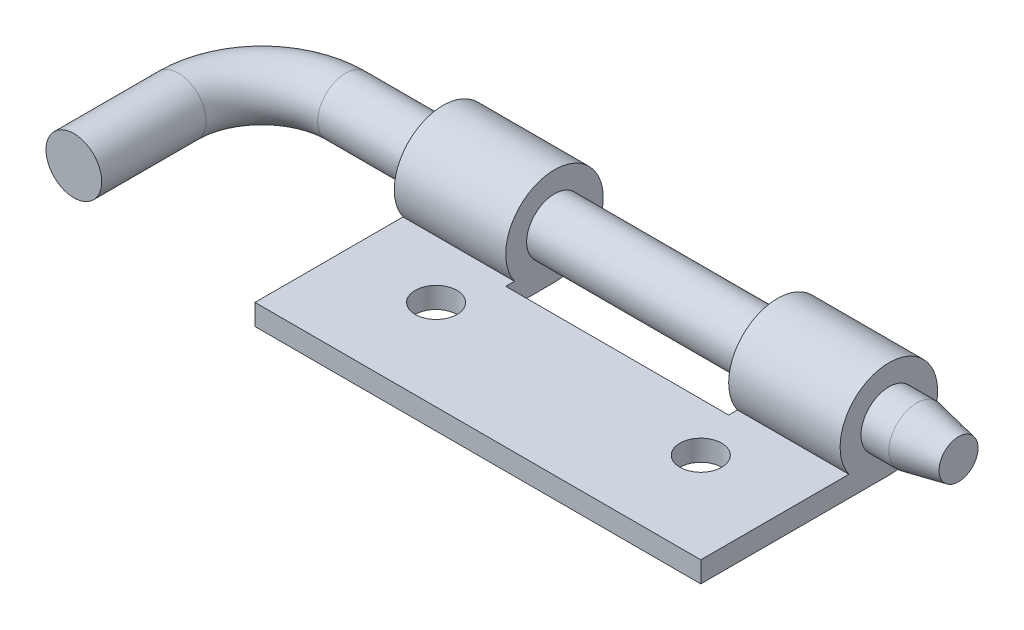
SolidWorks part; units mm, degrees
ref_plane "前视基准面" through (0, 0, 0) normal (0, 0, 1) x (1, 0, 0)
ref_plane "上视基准面" through (0, 0, 0) normal (0, 1, 0) x (1, 0, 0)
ref_plane "右视基准面" through (0, 0, 0) normal (1, 0, 0) x (0, 0, -1)
other "Configuration Table"
sketch "草图6" plane through (0, 0, 0) normal (1, 0, 0) x (0, 0, -1)
  circle A0 centre (0, 0) radius 3.5
  dimension "D1" = 7
extrude "凸台-拉伸4" add sketch "草图6" along normal blind 8
sketch "草图7" plane through (0, 0, 0) normal (-1, 0, 0) x (0, 0, 1)
  circle A0 centre (0, 0) radius 3.5 construction
  circle A1 centre (0, 0) radius 3.5
extrude "凸台-拉伸5" add sketch "草图7" against normal blind 8 from offset 24 separate body offset against normal yes
sketch "草图8" plane through (0, 0, 0) normal (0, 1, 0) x (1, 0, 0)
  line L0 (32, 3.5) -> (24, 3.5) construction
  line L1 (0, 0) -> (8, 0)
  line L2 (0, 0) -> (0, -13.5)
  line L3 (0, -13.5) -> (32, -13.5)
  line L4 (32, 0) -> (32, -13.5)
  line L5 (8, 0) -> (8, -3.5)
  line L6 (8, -3.5) -> (8, 3.5) construction
  line L7 (8, -3.5) -> (24, -3.5)
  line L8 (24, -3.5) -> (24, 0)
  line L9 (24, 3.5) -> (24, -3.5) construction
  line L10 (24, -3.5) -> (32, -3.5) construction
  line L11 (24, 0) -> (32, 0)
  circle A0 centre (25.5, -7) radius 1.5
  circle A1 centre (6.5, -7) radius 1.5
  point P9 (25.5, -8.5)
  point P10 (27, -7)
  dimension "D5" = 3
  dimension "D6" = 3
  dimension "D1" = 32
  dimension "D2" = 17
  dimension "D3" = 5
  dimension "D4" = 5
  dimension "D7" = 19
extrude "凸台-拉伸6" add sketch "草图8" along normal blind 1.5 from offset 3.5 offset against normal yes
sketch "草图9" plane through (0, 0, 0) normal (0, 1, 0) x (1, 0, 0)
  line L0 (37, 0) -> (-7, 0)
  line L1 (-13, -6) -> (-13, -13.5)
  line L6 (32, -3.5) -> (32, 3.5) construction
  line L7 (0, -13.5) -> (32, -13.5) construction
  arc A0 (-7, 0) -> (-13, -6) centre (-7, -6) ccw
  point P10 (0, 0)
  dimension "D3" = 6
  dimension "D1" = 5
  dimension "D2" = 50
ref_plane "基准面2" through (37, 0, 0) normal (1, 0, 0) x (0, 0, -1)
sketch "草图11" plane through (37, 0, 0) normal (1, 0, 0) x (0, 0, -1)
  circle A0 centre (0, 0) radius 2
  dimension "D1" = 4
sweep "扫描2" add profiles "草图11" path "草图9"
sketch "草图12" plane through (0, 0, 0) normal (0, 1, 0) x (1, 0, 0)
  line L0 (34, -2) -> (34, 2)
  line L1 (-3.85, 0) -> (3.85, 0) construction
  line L2 (37, 2) -> (32, 2) construction
  line L3 (34, 2) -> (37, 1.4)
  line L4 (37, -55) -> (37, 55) construction
  line L5 (37, 1.4) -> (37, -1.4)
  line L6 (34, -2) -> (37, -1.4)
  line L7 (34, 2) -> (37, 2)
  line L8 (37, 2) -> (37, 1.4)
  line L9 (37, -1.4) -> (37, -2)
  line L10 (32, -2) -> (37, -2) construction
  line L11 (37, -2) -> (34, -2)
  line L12 (39.1544, 0) -> (47.1528, 0) construction
  point P11 (37, 0)
  point P12 (34, 0)
  dimension "D1" = 2.8
  dimension "D2" = 3
revolve "切除-旋转1" cut sketch "草图12" angle 360 about L12
